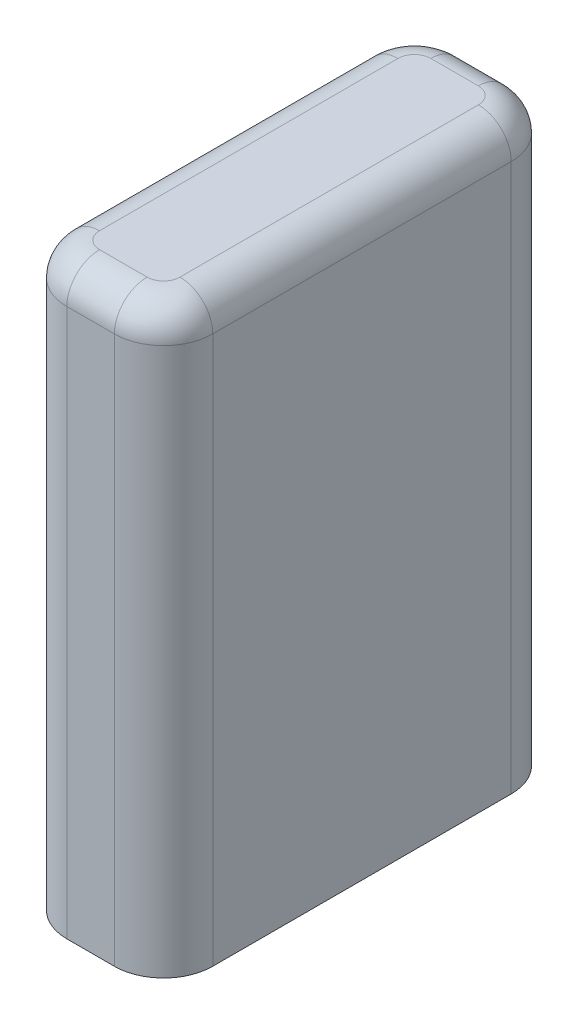
SolidWorks part; units mm, degrees
ref_plane "Front Plane" through (0, 0, 0) normal (0, 0, 1) x (1, 0, 0)
ref_plane "Top Plane" through (0, 0, 0) normal (0, 1, 0) x (1, 0, 0)
ref_plane "Right Plane" through (0, 0, 0) normal (1, 0, 0) x (0, 0, -1)
sketch "Sketch1" plane through (0, 0, 0) normal (0, 1, 0) x (1, 0, 0)
  line L1 (-0.9326, 13.0395) -> (1.9674, 13.0395)
  line L2 (-3.9326, 10.0395) -> (-3.9326, -8.1605)
  line L3 (-0.9326, -11.1605) -> (1.9674, -11.1605)
  line L4 (4.9674, 10.0395) -> (4.9674, -8.1605)
  arc A0 (4.9674, -8.1605) -> (1.9674, -11.1605) centre (1.9674, -8.1605) cw
  arc A1 (-0.9326, -11.1605) -> (-3.9326, -8.1605) centre (-0.9326, -8.1605) cw
  arc A2 (-3.9326, 10.0395) -> (-0.9326, 13.0395) centre (-0.9326, 10.0395) cw
  arc A3 (4.9674, 10.0395) -> (1.9674, 13.0395) centre (1.9674, 10.0395) ccw
  point P6 (4.9674, -11.1605)
  point P11 (-3.9326, 13.0395)
  point P14 (4.9674, 13.0395)
  dimension "D3" = 3
  dimension "D1" = 8.9
  dimension "D2" = 24.2
extrude "Boss-Extrude1" add sketch "Sketch1" along normal blind 35.4
fillet "Fillet1" radius 2 8 edges at (-3.9326, 35.4, -0.9395) (-3.0539, 35.4, -12.1609) (0.5174, 35.4, -13.0395) (4.0888, 35.4, -12.1609) (4.9674, 35.4, -0.9395) (-3.0539, 35.4, 10.2818) (0.5174, 35.4, 11.1605) (4.0888, 35.4, 10.2818)
